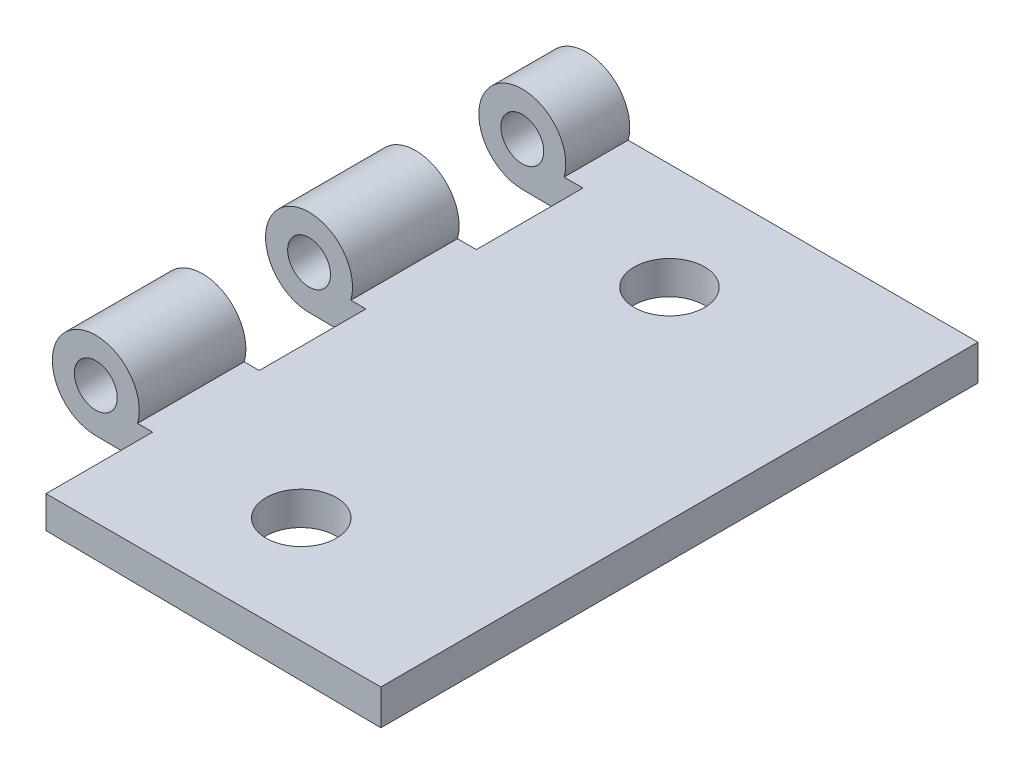
SolidWorks part; units mm, degrees
ref_plane "前视基准面" through (0, 0, 0) normal (0, 0, 1) x (1, 0, 0)
ref_plane "上视基准面" through (0, 0, 0) normal (0, 1, 0) x (1, 0, 0)
ref_plane "右视基准面" through (0, 0, 0) normal (1, 0, 0) x (0, 0, -1)
other "Configuration Table"
sketch "草图25" plane through (0, 0, 0) normal (0, 0, 1) x (1, 0, 0)
  line L0 (0, -20.387) -> (183.6747, -22.2015)
  line L1 (183.6747, -22.2015) -> (183.6747, -5.6172)
  line L2 (183.6747, -5.6172) -> (19.5979, -5.6172)
  arc A0 (19.5979, -5.6172) -> (0, -20.387) centre (0, 0) ccw
  circle A1 centre (0, 0) radius 10.0437
extrude "凸台-拉伸13" add sketch "草图25" along normal blind 280 contours A1 | L2 A0 L0 L1
sketch "草图26" plane through (0, -5.6172, 0) normal (0, 1, 0) x (1, 0, 0)
  line L0 (183.6747, 0) -> (19.5979, 0) construction
  line L1 (183.6747, -280) -> (19.5979, -280) construction
  circle A0 centre (88.9974, -50) radius 16.5051
  circle A1 centre (96.351, -230) radius 16.5051
  dimension "D1" = 50
  dimension "D2" = 50
extrude "切除-拉伸3" cut sketch "草图26" against normal through all
sketch "草图27" plane through (0, -5.6172, 0) normal (0, 1, 0) x (1, 0, 0)
  line L0 (-20.387, -280) -> (20.387, -280) construction
  line L1 (-42.2136, -30) -> (28.452, -30)
  line L2 (-42.2136, -30) -> (-42.2136, -80)
  line L3 (-42.2136, -80) -> (28.452, -80)
  line L4 (28.452, -30) -> (28.452, -80)
  line L5 (-42.2136, -130) -> (26.6532, -130)
  line L6 (-42.2136, -130) -> (-42.2136, -180)
  line L7 (-42.2136, -180) -> (26.6532, -180)
  line L8 (26.6532, -130) -> (26.6532, -180)
  line L9 (-42.2136, -230) -> (26.6532, -230)
  line L10 (-42.2136, -230) -> (-42.2136, -280)
  line L11 (-42.2136, -280) -> (26.6532, -280)
  line L12 (26.6532, -230) -> (26.6532, -280)
  dimension "D1" = 50
  dimension "D2" = 68.8668
  dimension "D3" = 50
  dimension "D4" = 50
  dimension "D5" = 50
  dimension "D6" = 68.8668
  dimension "D7" = 68.8668
  dimension "D8" = 0
  dimension "D9" = 50
extrude "切除-拉伸4" cut sketch "草图27" against normal through all and the other way through all contours L2 L3 L4 L1 | L9 L12 L11 L10 | L8 L7 L6 L5
